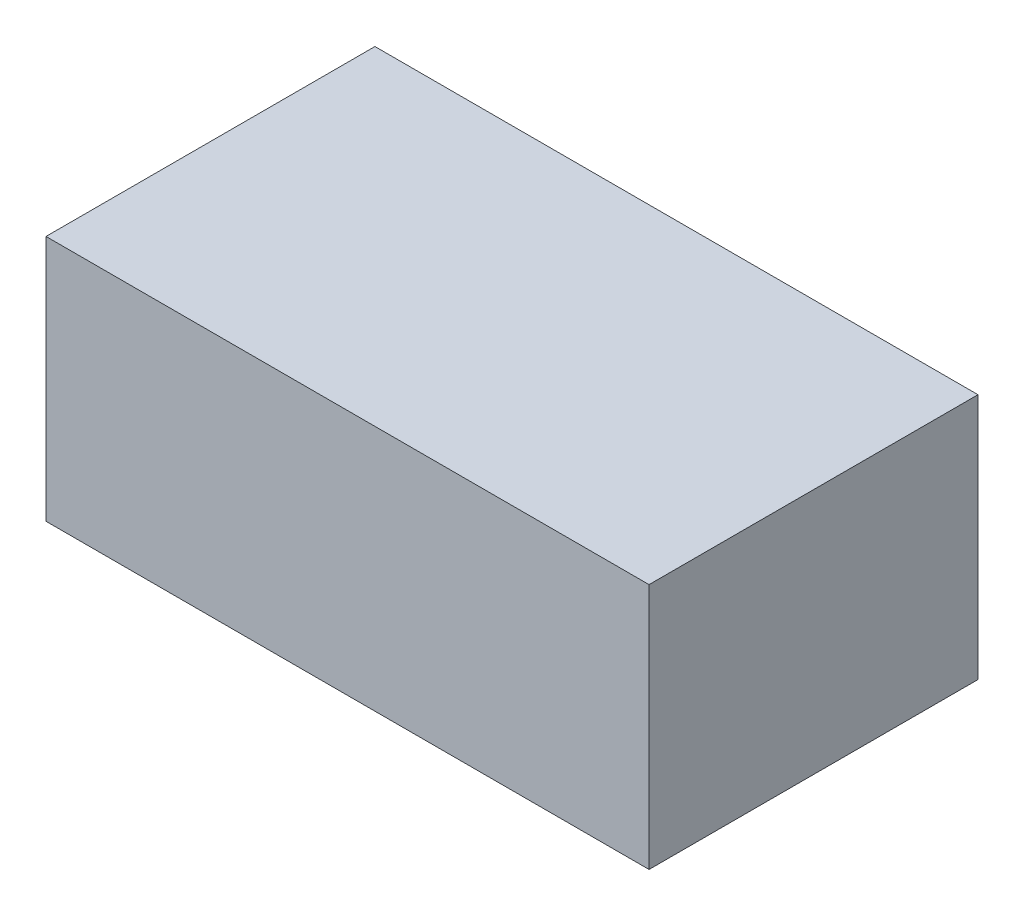
SolidWorks part; units mm, degrees
ref_plane "Front Plane" through (0, 0, 0) normal (0, 0, 1) x (1, 0, 0)
ref_plane "Top Plane" through (0, 0, 0) normal (0, 1, 0) x (1, 0, 0)
ref_plane "Right Plane" through (0, 0, 0) normal (1, 0, 0) x (0, 0, -1)
sketch "Sketch1" plane through (0, 0, 0) normal (0, 1, 0) x (1, 0, 0)
  line L1 (55, -30) -> (-55, -30)
  line L2 (55, -30) -> (55, 30)
  line L3 (55, 30) -> (-55, 30)
  line L4 (-55, -30) -> (-55, 30)
  line L5 (55, -30) -> (-55, 30) construction
  line L6 (55, 30) -> (-55, -30) construction
  point P0 (0, 0)
extrude "Boss-Extrude1" add sketch "Sketch1" along normal blind 45
